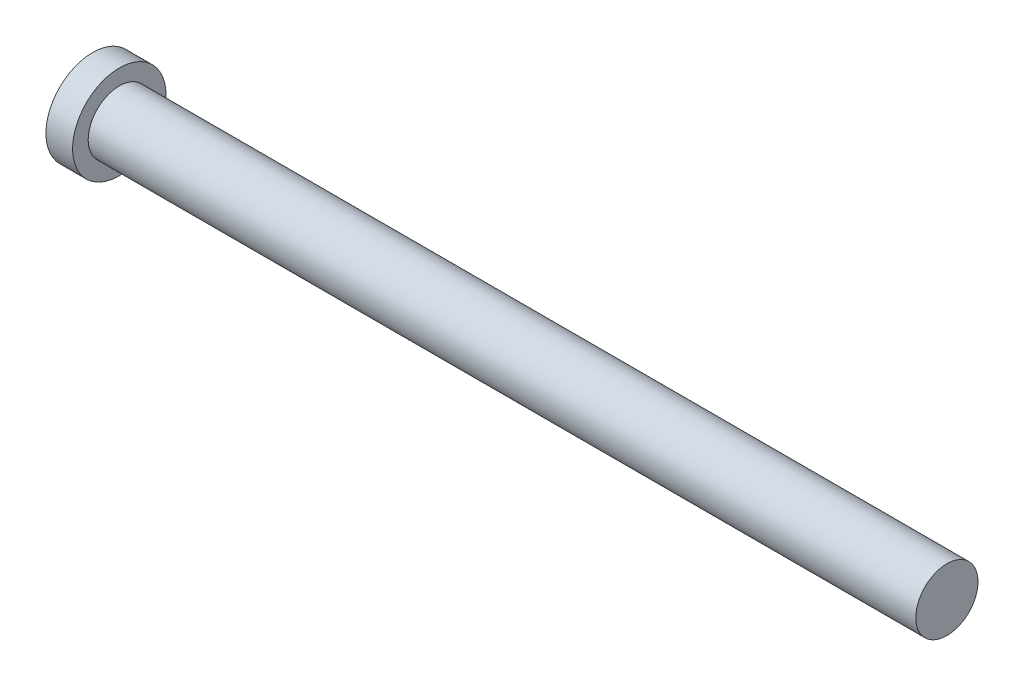
SolidWorks part; units mm, degrees
material "AISI 316 Stainless Steel Sheet (SS)"
ref_plane "Front Plane" through (0, 0, 0) normal (0, 0, 1) x (1, 0, 0)
ref_plane "Top Plane" through (0, 0, 0) normal (0, 1, 0) x (1, 0, 0)
ref_plane "Right Plane" through (0, 0, 0) normal (1, 0, 0) x (0, 0, -1)
sketch "Sketch1" plane through (0, 0, 0) normal (1, 0, 0) x (0, 0, -1)
  circle A0 centre (0, 0) radius 5.25
  dimension "D1" = 10.5
extrude "Boss-Extrude1" add sketch "Sketch1" along normal blind 3
sketch "Sketch2" plane through (3, 0, 0) normal (1, 0, 0) x (0, 0, -1)
  circle A0 centre (0, 0) radius 3.5
extrude "Boss-Extrude2" add sketch "Sketch2" along normal blind 93
